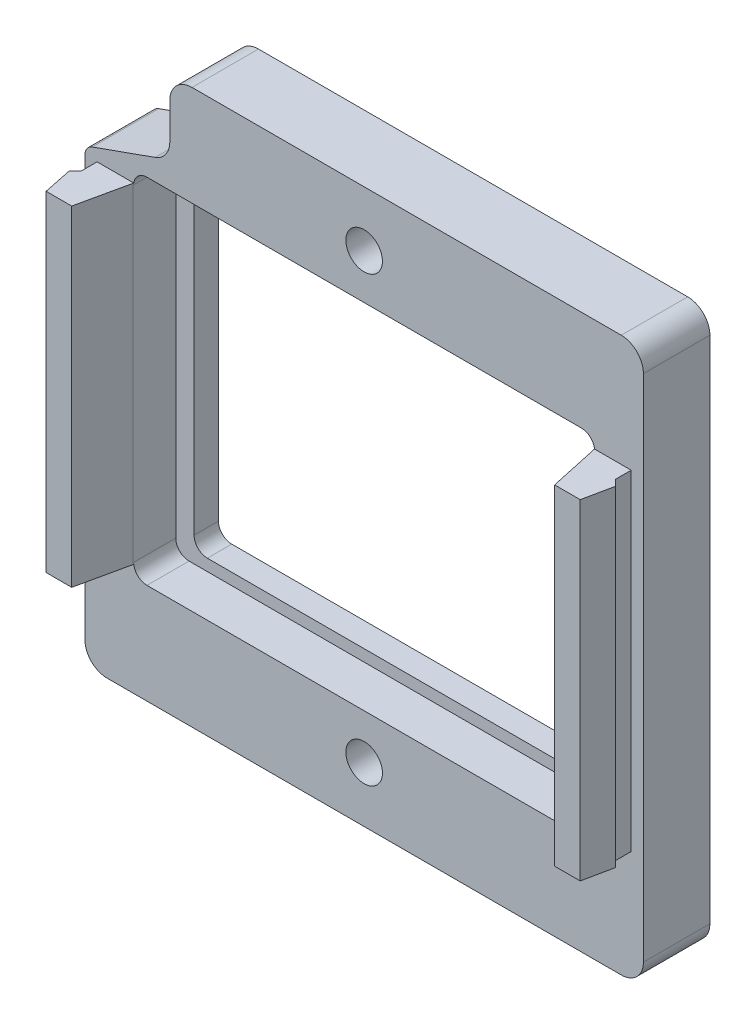
SolidWorks part; units mm, degrees
ref_plane "Front Plane" through (0, 0, 0) normal (0, 0, 1) x (1, 0, 0)
ref_plane "Top Plane" through (0, 0, 0) normal (0, 1, 0) x (1, 0, 0)
ref_plane "Right Plane" through (0, 0, 0) normal (1, 0, 0) x (0, 0, -1)
sketch "Sketch1" plane through (0, 0, 0) normal (0, 0, 1) x (1, 0, 0)
  line L9 (-19.15, -13.7) -> (-19.15, 13.7)
  line L10 (-17.95, -14.9) -> (17.95, -14.9)
  line L11 (19.15, -13.7) -> (19.15, 13.7)
  line L12 (-17.95, 14.9) -> (17.95, 14.9)
  line L23 (-17.5363, 19.7512) -> (-17.5363, 23)
  line L24 (-15.5363, 25) -> (23.2, 25)
  line L25 (-24.5363, 15.8417) -> (-18.8637, 17.8677)
  line L26 (25.2, 23) -> (25.2, -23)
  line L28 (23.2, -25) -> (-23.2, -25)
  line L29 (-25.2, 14.9) -> (-25.2, -23)
  arc A6 (19.15, 13.7) -> (17.95, 14.9) centre (17.95, 13.7) ccw
  arc A7 (17.95, -14.9) -> (19.15, -13.7) centre (17.95, -13.7) ccw
  arc A8 (-19.15, -13.7) -> (-17.95, -14.9) centre (-17.95, -13.7) ccw
  arc A9 (-19.15, 13.7) -> (-17.95, 14.9) centre (-17.95, 13.7) cw
  circle A10 centre (0, 20) radius 1.65
  circle A11 centre (0, -20) radius 1.65
  arc A17 (-18.8637, 17.8677) -> (-17.5363, 19.7512) centre (-19.5363, 19.7512) ccw
  arc A18 (-17.5363, 23) -> (-15.5363, 25) centre (-15.5363, 23) cw
  arc A19 (-25.2, 14.9) -> (-24.5363, 15.8417) centre (-24.2, 14.9) cw
  arc A22 (23.2, -25) -> (25.2, -23) centre (23.2, -23) ccw
  arc A23 (25.2, 23) -> (23.2, 25) centre (23.2, 23) ccw
  arc A24 (-23.2, -25) -> (-25.2, -23) centre (-23.2, -23) cw
extrude "Boss-Extrude1" add sketch "Sketch1" along normal blind 10.6
sketch "Sketch2" plane through (0, 0, 10.6) normal (0, 0, 1) x (1, 0, 0)
  line L11 (-25.2, 14.9) -> (25.2, 14.9)
  line L12 (-25.2, 14.9) -> (-25.2, -14.9)
  line L13 (-25.2, -14.9) -> (25.2, -14.9)
  line L14 (25.2, 14.9) -> (25.2, -14.9)
extrude "Cut-Extrude1" cut sketch "Sketch2" against normal blind 4.6 flip side to cut
sketch "Sketch3" plane through (0, 0, 10.6) normal (0, 0, 1) x (1, 0, 0)
  line L10 (-20.8, -14.75) -> (-20.8, 14.75)
  line L11 (-19.6, -15.95) -> (19.6, -15.95)
  line L12 (20.8, -14.75) -> (20.8, 14.75)
  line L13 (-19.6, 15.95) -> (19.6, 15.95)
  arc A3 (19.6, -15.95) -> (20.8, -14.75) centre (19.6, -14.75) ccw
  arc A4 (-20.8, -14.75) -> (-19.6, -15.95) centre (-19.6, -14.75) ccw
  arc A5 (20.8, 14.75) -> (19.6, 15.95) centre (19.6, 14.75) ccw
  arc A6 (-20.8, 14.75) -> (-19.6, 15.95) centre (-19.6, 14.75) cw
extrude "Cut-Extrude2" cut sketch "Sketch3" against normal offset from surface (8.4 mm away) 2.2 up to face at (-5.8883, 5.688, 0)
sketch "Sketch4" plane through (0, -25, 0) normal (0, -1, 0) x (1, 0, 0)
  line L9 (-24.1, 7.4) -> (-24.65, 7.95)
  line L11 (-24.1, 10.6) -> (-21.7906, 10.6)
  line L14 (24.1, 6) -> (25.2, 6)
  line L15 (-25.2, 0) -> (25.2, 0)
  line L16 (-25.2, 0) -> (-25.2, 6)
  line L17 (-25.2, 6) -> (-24.1, 6)
  line L18 (25.2, 0) -> (25.2, 6)
  line L20 (24.1, 6) -> (24.1, 7.4)
  line L22 (-24.1, 6) -> (-24.1, 7.4)
  line L23 (-24.65, 7.95) -> (-24.1, 10.6)
  line L24 (24.1, 7.4) -> (24.65, 7.95)
  line L25 (24.65, 7.95) -> (24.1, 10.6)
  line L27 (-21.7906, 10.6) -> (-20.7906, 6)
  line L30 (21.7906, 10.6) -> (20.7906, 6)
  line L31 (-20.7906, 6) -> (20.7906, 6)
  line L32 (21.7906, 10.6) -> (24.1, 10.6)
extrude "Cut-Extrude3" cut sketch "Sketch4" against normal up to surface (50 mm away) flip side to cut up to face at (3.8318, 25, 3)
